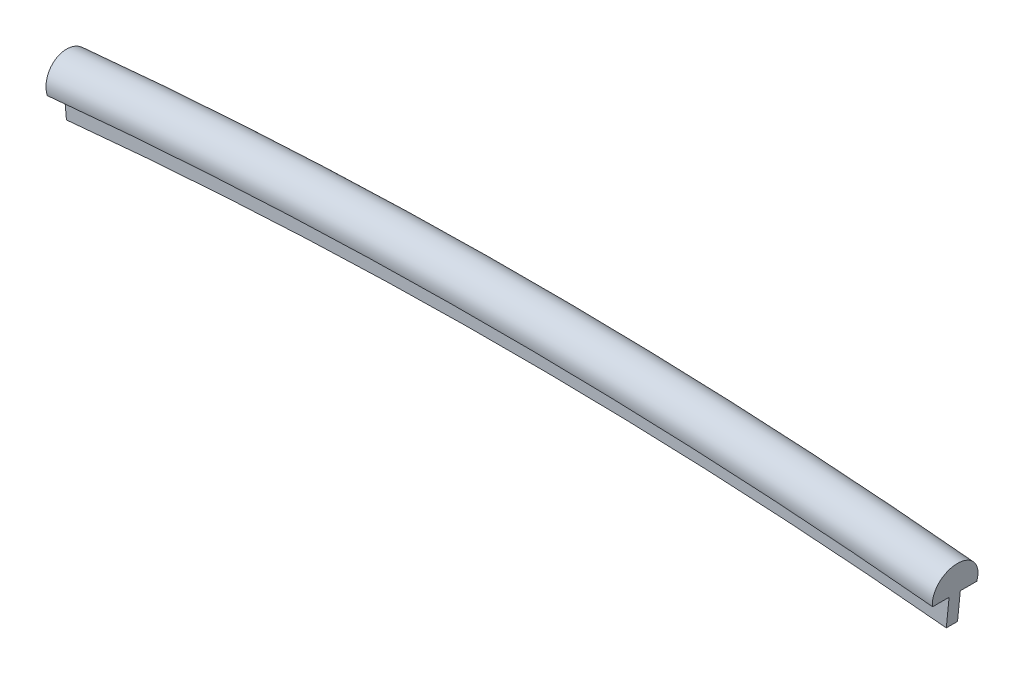
SolidWorks part; units mm, degrees
ref_plane "Front Plane" through (0, 0, 0) normal (0, 0, 1) x (1, 0, 0)
ref_plane "Top Plane" through (0, 0, 0) normal (0, 1, 0) x (1, 0, 0)
ref_plane "Right Plane" through (0, 0, 0) normal (1, 0, 0) x (0, 0, -1)
sketch "Sketch2" plane through (0, 0, 0) normal (1, 0, 0) x (0, 0, -1)
  line L0 (0, 241.3) -> (0, 0) construction
  line L2 (0, 241.3) -> (0, 239.8) construction
  line L3 (0, 239.8) -> (0.3, 239.8)
  line L4 (0, 239.8) -> (-0.3, 239.8)
  line L5 (-0.3, 239.8) -> (-0.3, 241.3)
  line L6 (0.3, 239.8) -> (0.3, 241.3)
  line L7 (0, 241.3) -> (0, 242.8) construction
  line L8 (-1.18, 241.3) -> (-0.3, 241.3)
  line L9 (0.3, 241.3) -> (1.18, 241.3)
  arc A0 (-1.18, 241.3) -> (1.18, 241.3) centre (0, 241.586) cw
  point P14 (0, 241.3)
ref_axis "Axis2" through (0, 0, 70.5976) along (0, 0, -1)
revolve "Revolve1" add sketch "Sketch2" angle 5.631 about axis through (0, 0, 70.5976) along (0, 0, -1)
